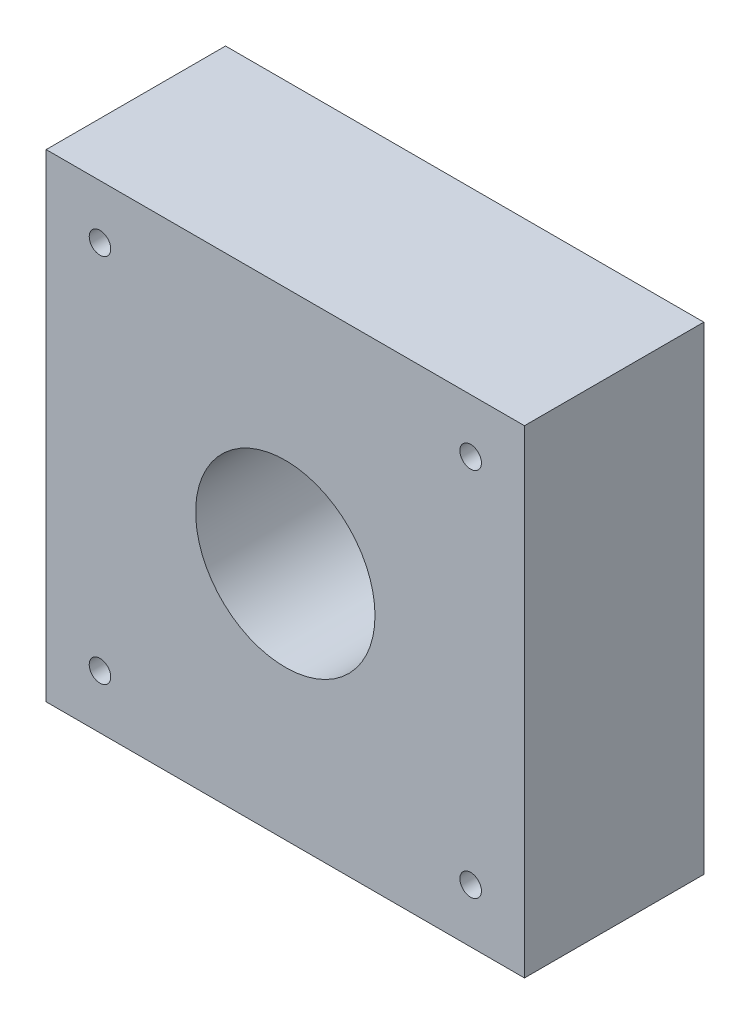
SolidWorks part; units mm, degrees
material "2.0060 (Cu-ETP)"
ref_plane "Ebene vorne" through (0, 0, 0) normal (0, 0, 1) x (1, 0, 0)
ref_plane "Ebene oben" through (0, 0, 0) normal (0, 1, 0) x (1, 0, 0)
ref_plane "Ebene rechts" through (0, 0, 0) normal (1, 0, 0) x (0, 0, -1)
sketch "Skizze1" plane through (0, 0, 0) normal (0, 0, 1) x (1, 0, 0)
  line L1 (-15.5208, 24.375) -> (24.4792, 24.375)
  line L2 (-15.5208, 24.375) -> (-15.5208, -15.625)
  line L3 (-15.5208, -15.625) -> (24.4792, -15.625)
  line L4 (24.4792, 24.375) -> (24.4792, -15.625)
  dimension "D1" = 40
  dimension "D2" = 40
extrude "Aufsatz-Linear austragen1" add sketch "Skizze1" along normal blind 15
sketch "Skizze3" plane through (0, 0, 15) normal (0, 0, 1) x (1, 0, 0)
  line L6 (-15.5208, -15.625) -> (24.4792, -15.625) construction
  line L7 (-15.5208, 24.375) -> (-15.5208, -15.625) construction
  circle A0 centre (4.4792, 4.375) radius 7.5
  dimension "D1" = 20
  dimension "D3" = 15
  dimension "D2" = 20
extrude "Schnitt-Linear austragen1" cut sketch "Skizze3" against normal blind 12
hole_wizard "Durchgangsloch für M41" positions "Skizze7" profile "Skizze8" hole size "M4" standard "DIN" end condition through all
sketch "Skizze7" plane through (0, 0, 3) normal (0, 0, 1) x (1, 0, 0)
  line L0 (-15.5208, 24.375) -> (-15.5208, -15.625) construction
  line L1 (24.4792, 24.375) -> (-15.5208, 24.375) construction
  point P0 (4.4792, 4.375)
  dimension "D1" = 20
  dimension "D2" = 20
sketch "Skizze8" plane through (4.4792, 4.375, 3) normal (1, 0, 0) x (0, -1, 0)
  line L0 (0, 0) -> (0, 3)
  line L1 (0, 3) -> (2.25, 3)
  line L2 (2.25, 3) -> (2.25, 0)
  line L5 (2.25, 0) -> (0, 0)
  line L11 (0, -6.35) -> (0, 107.95) construction
  dimension "Bohrerdurchmesser" = 4.5
  dimension "Bohrungstiefe" = 3
hole_wizard "Durchgangsloch für M1.61" positions "Skizze10" profile "Skizze11" hole size "M1.6" standard "DIN" end condition through all
sketch "Skizze10" plane through (0, 0, 3) normal (0, 0, 1) x (1, 0, 0)
  line L0 (-15.5208, 24.375) -> (-15.5208, -15.625) construction
  circle A0 centre (4.4792, 4.375) radius 2.25 construction
  point P0 (4.4792, 8.875)
  point P2 (4.4792, -0.125)
  dimension "D1" = 20
  dimension "D2" = 20
  dimension "D3" = 4.5
  dimension "D4" = 4.5
sketch "Skizze11" plane through (4.4792, 8.875, 3) normal (1, 0, 0) x (0, -1, 0)
  line L0 (0, 0) -> (0, 3)
  line L1 (0, 3) -> (0.9, 3)
  line L2 (0.9, 3) -> (0.9, 0)
  line L5 (0.9, 0) -> (0, 0)
  line L11 (0, -6.35) -> (0, 107.95) construction
  dimension "Bohrerdurchmesser" = 1.8
  dimension "Bohrungstiefe" = 3
hole_wizard "Formsenkung für M1.6 Senkschraube mit Schlitz/Kreuzschlitz1" positions "Skizze12" profile "Skizze13" countersink size "M1.6" standard "DIN" end condition through all
sketch "Skizze12" plane through (0, 0, 0) normal (0, 0, -1) x (-1, 0, 0)
  line L0 (-24.4792, -15.625) -> (-24.4792, 24.375) construction
  line L1 (15.5208, -15.625) -> (-24.4792, -15.625) construction
  line L2 (-24.4792, 24.375) -> (15.5208, 24.375) construction
  line L3 (15.5208, 24.375) -> (15.5208, -15.625) construction
  point P0 (-19.9792, 19.875)
  point P2 (11.0208, 19.875)
  point P4 (11.0208, -11.125)
  point P6 (-19.9792, -11.125)
  dimension "D1" = 4.5
  dimension "D2" = 4.5
  dimension "D3" = 4.5
  dimension "D4" = 4.5
  dimension "D5" = 4.5
  dimension "D6" = 4.5
  dimension "D7" = 4.5
  dimension "D8" = 4.5
sketch "Skizze13" plane through (19.9792, 19.875, 0) normal (1, 0, 0) x (0, 1, 0)
  line L0 (0, 0) -> (0, 15)
  line L1 (0, 15) -> (0.9, 15)
  line L2 (0.9, 15) -> (0.9, 0.9)
  line L3 (0.9, 0.9) -> (1.8, 0)
  line L5 (1.8, 0) -> (0, 0)
  line L6 (-0.9, 0.9) -> (-1.8, 0) construction
  line L11 (0, -6.35) -> (0, 107.95) construction
  dimension "Bohrerdurchmesser" = 1.8
  dimension "Bohrungstiefe" = 15
  dimension "Senkdurchmesser (Oben)" = 3.6
  dimension "Senkwinkel (Oben)" = 90
